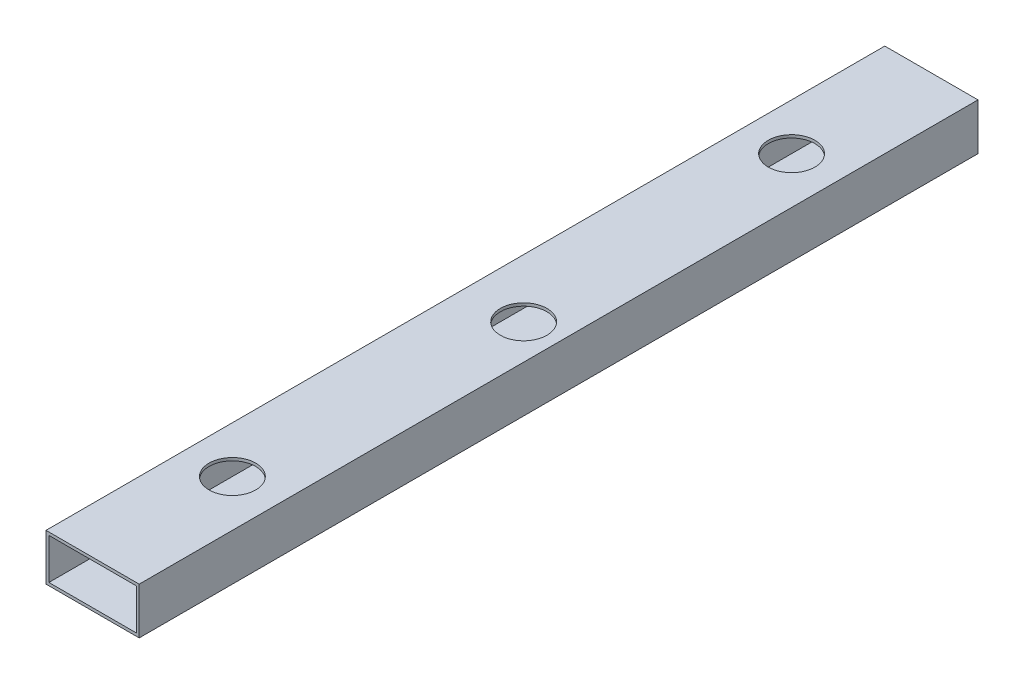
SolidWorks part; units mm, degrees
ref_plane "Front Plane" through (0, 0, 0) normal (0, 0, 1) x (1, 0, 0)
ref_plane "Top Plane" through (0, 0, 0) normal (0, 1, 0) x (1, 0, 0)
ref_plane "Right Plane" through (0, 0, 0) normal (1, 0, 0) x (0, 0, -1)
sketch "Sketch1" plane through (0, 0, 0) normal (0, 0, 1) x (1, 0, 0)
  line L0 (1.5875, 23.8125) -> (49.2125, 23.8125)
  line L1 (0, 0) -> (50.8, 0)
  line L2 (0, 0) -> (0, 25.4)
  line L3 (0, 25.4) -> (50.8, 25.4)
  line L4 (50.8, 0) -> (50.8, 25.4)
  line L5 (49.2125, 1.5875) -> (49.2125, 23.8125)
  line L6 (1.5875, 1.5875) -> (49.2125, 1.5875)
  line L7 (1.5875, 1.5875) -> (1.5875, 23.8125)
  dimension "D1" = 25.4
  dimension "D2" = 50.8
  dimension "D3" = 1.5875
extrude "Boss-Extrude1" add sketch "Sketch1" along normal blind 457.2
sketch "Sketch2" plane through (0, 25.4, 0) normal (0, 1, 0) x (1, 0, 0)
  line L0 (0, -457.2) -> (0, 0)
  line L6 (25.4, -381) -> (25.4, -457.2)
  line L7 (50.8, -457.2) -> (0, -457.2) construction
  line L8 (25.4, -457.2) -> (25.4, -381)
  circle A0 centre (25.4, -381) radius 12.7
  dimension "D4" = 25.4
  dimension "D1" = 76.2
extrude "Cut-Extrude1" cut sketch "Sketch2" against normal blind 25.4 contours A0
sketch "Sketch4" plane through (0, 25.4, 0) normal (0, 1, 0) x (1, 0, 0)
  line L0 (25.4, 0) -> (25.4, -76.2)
  line L1 (50.8, 0) -> (0, 0) construction
  circle A0 centre (25.4, -76.2) radius 12.7
  dimension "D2" = 25.4
  dimension "D1" = 76.2
extrude "Cut-Extrude2" cut sketch "Sketch4" against normal blind 25.4
sketch "Sketch5" plane through (0, 25.4, 0) normal (0, 1, 0) x (1, 0, 0)
  line L0 (0, -228.6) -> (31.75, -228.6)
  line L2 (0, -457.2) -> (0, 0) construction
  circle A0 centre (31.75, -228.6) radius 12.7
  dimension "D2" = 25.4
  dimension "D1" = 31.75
extrude "Cut-Extrude5" cut sketch "Sketch5" against normal blind 25.4
equation "\"1i\"=0.1"
